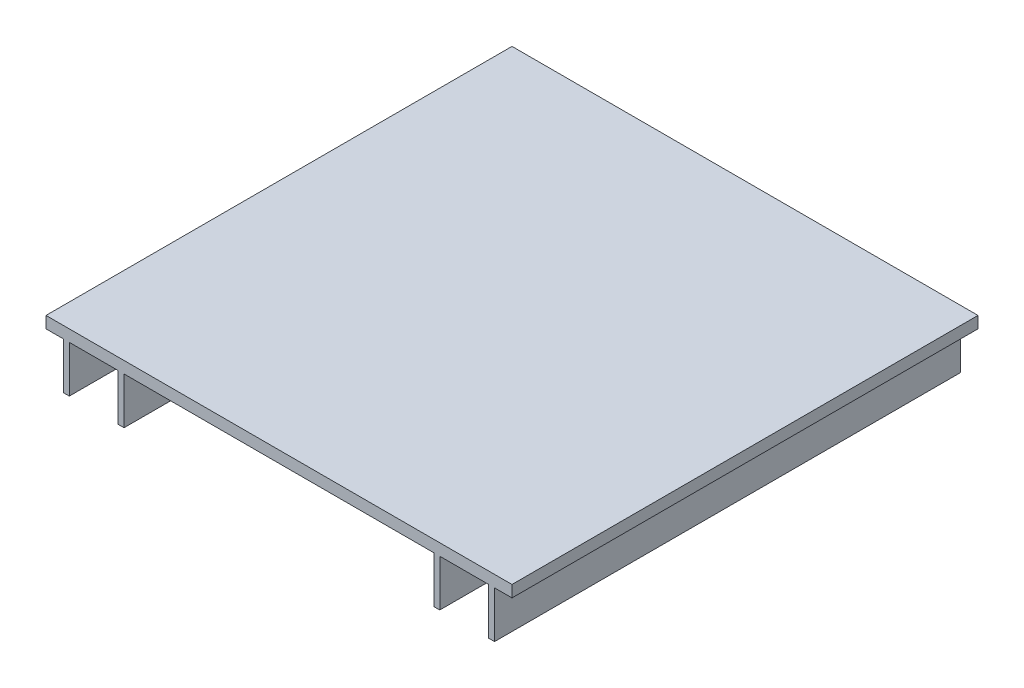
SolidWorks part; units mm, degrees
ref_plane "前视基准面" through (0, 0, 0) normal (0, 0, 1) x (1, 0, 0)
ref_plane "上视基准面" through (0, 0, 0) normal (0, 1, 0) x (1, 0, 0)
ref_plane "右视基准面" through (0, 0, 0) normal (1, 0, 0) x (0, 0, -1)
sketch "草图1" plane through (0, 0, 0) normal (0, 1, 0) x (1, 0, 0)
  line L1 (-100, 100) -> (100, 100)
  line L2 (-100, 100) -> (-100, -100)
  line L3 (-100, -100) -> (100, -100)
  line L4 (100, 100) -> (100, -100)
  line L5 (0, -100) -> (0, 100) construction
  line L6 (-100, 0) -> (100, 0) construction
  point P0 (0, 0)
  dimension "D1" = 200
  dimension "D2" = 200
extrude "凸台-拉伸1" add sketch "草图1" along normal blind 5
sketch "草图2" plane through (0, 0, 0) normal (0, -1, 0) x (1, 0, 0)
  line L0 (0, 0) -> (0, 80.4527) construction
  line L1 (-69, 100) -> (-69, -100)
  line L2 (-100, 100) -> (100, 100) construction
  line L3 (100, -100) -> (-100, -100) construction
  line L4 (-69, -100) -> (-66.5, -100)
  line L5 (-66.5, -100) -> (-66.5, 100)
  line L6 (-66.5, 100) -> (-69, 100)
  line L7 (-90, 100) -> (-90, -100)
  line L8 (-92.5, -100) -> (-92.5, 100)
  line L9 (-92.5, 100) -> (-90, 100)
  line L10 (-92.5, -100) -> (-90, -100)
  dimension "D1" = 69
  dimension "D2" = 2.5
  dimension "D3" = 21
  dimension "D4" = 2.5
extrude "凸台-拉伸2" add sketch "草图2" along normal blind 20
mirror "镜向1" about plane through (0, 0, 0) normal (1, 0, 0) of "凸台-拉伸2"
